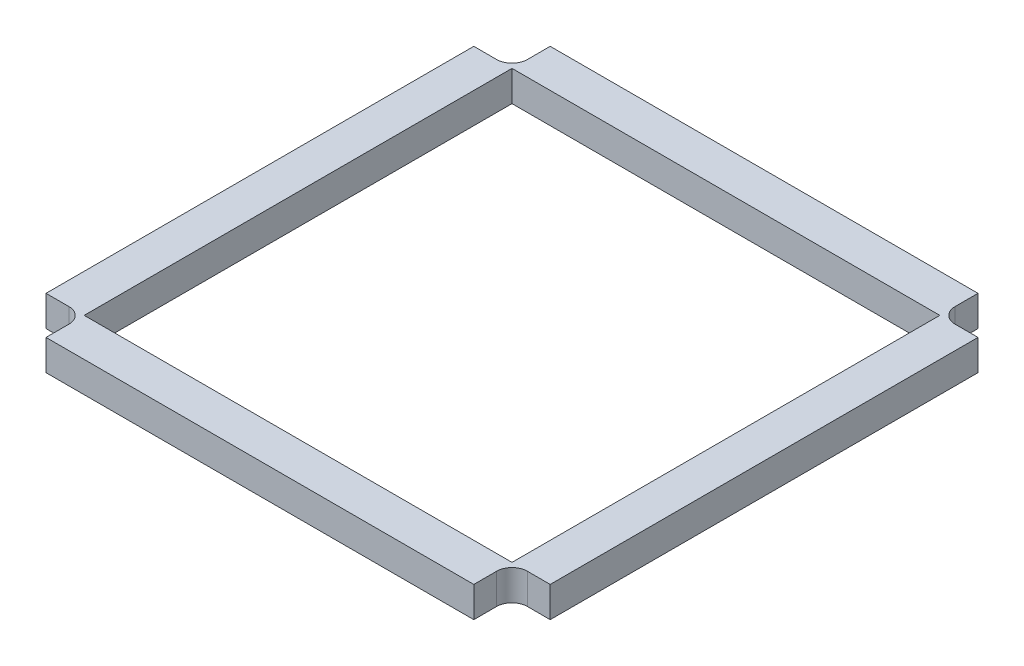
SolidWorks part; units mm, degrees
ref_plane "Alzado" through (0, 0, 0) normal (0, 0, 1) x (1, 0, 0)
ref_plane "Planta" through (0, 0, 0) normal (0, 1, 0) x (1, 0, 0)
ref_plane "Vista lateral" through (0, 0, 0) normal (1, 0, 0) x (0, 0, -1)
sketch "Croquis1" plane through (0, 0, 0) normal (0, 1, 0) x (1, 0, 0)
  line L0 (70, 152.5) -> (70, -12.5) construction
  line L1 (0, 0) -> (140, 0)
  line L2 (0, 0) -> (0, 140)
  line L3 (0, 140) -> (140, 140)
  line L4 (140, 0) -> (140, 140)
  line L5 (-12.5, -12.5) -> (152.5, -12.5)
  line L6 (-12.5, -12.5) -> (-12.5, 152.5)
  line L7 (-12.5, 152.5) -> (152.5, 152.5)
  line L8 (152.5, -12.5) -> (152.5, 152.5)
  line L9 (0, 70) -> (140, 70) construction
  line L11 (145, -5) -> (-5, -5) construction
  line L12 (145, -5) -> (145, 145) construction
  line L13 (145, 145) -> (-5, 145) construction
  line L14 (-5, -5) -> (-5, 145) construction
  line L15 (145, -5) -> (-5, 145) construction
  line L16 (145, 145) -> (-5, -5) construction
  point P13 (70, 70)
  point P14 (70, 70)
  point P15 (70, 70)
  point P20 (146.2548, -6.2548)
  dimension "D1" = 140
  dimension "D2" = 165
  dimension "D3" = 150
extrude "Saliente-Extruir1" add sketch "Croquis1" along normal blind 10
sketch "Croquis2" plane through (0, 10, 0) normal (0, 1, 0) x (1, 0, 0)
  line L0 (0, 70) -> (140, 70) construction
  line L1 (0, 140) -> (0, 0) construction
  line L2 (140, 0) -> (140, 140) construction
  line L3 (70, 70) -> (70, 140) construction
  line L4 (140, 140) -> (0, 140) construction
  line L5 (0, 145) -> (0, 152.5)
  line L6 (145, -5) -> (-5, -5) construction
  line L7 (145, -5) -> (145, 145) construction
  line L8 (145, 145) -> (-5, 145) construction
  line L9 (-5, -5) -> (-5, 145) construction
  line L10 (145, -5) -> (-5, 145) construction
  line L11 (145, 145) -> (-5, -5) construction
  line L12 (145, 140) -> (152.5, 140)
  line L13 (152.5, 140) -> (152.5, 152.5)
  line L14 (0, 152.5) -> (-12.5, 152.5)
  line L15 (-5, 140) -> (-12.5, 140)
  line L16 (152.5, 152.5) -> (140, 152.5)
  line L17 (140, 145) -> (140, 152.5)
  line L18 (-12.5, 152.5) -> (-12.5, -12.5) construction
  line L19 (-12.5, 152.5) -> (-12.5, 140)
  line L20 (140, -5) -> (140, -12.5)
  line L21 (140, -12.5) -> (152.5, -12.5)
  line L22 (152.5, -12.5) -> (152.5, 0)
  line L23 (145, 0) -> (152.5, 0)
  line L24 (-5, 0) -> (-12.5, 0)
  line L25 (-12.5, 0) -> (-12.5, -12.5)
  line L26 (-12.5, -12.5) -> (0, -12.5)
  line L27 (0, -5) -> (0, -12.5)
  arc A0 (-5, 140) -> (0, 145) centre (-5, 145) ccw
  arc A1 (140, 145) -> (145, 140) centre (145, 145) ccw
  arc A2 (145, 0) -> (140, -5) centre (145, -5) ccw
  arc A3 (0, -5) -> (-5, 0) centre (-5, -5) ccw
  dimension "D2" = 10
  dimension "D1" = 150
  dimension "D3" = 4
extrude "Cortar-Extruir1" cut sketch "Croquis2" against normal blind 10 contours A0 L5 L14 L19 L15 | L24 L25 L26 L27 A3 | L20 L21 L22 L23 A2 | L12 L13 L16 L17 A1
